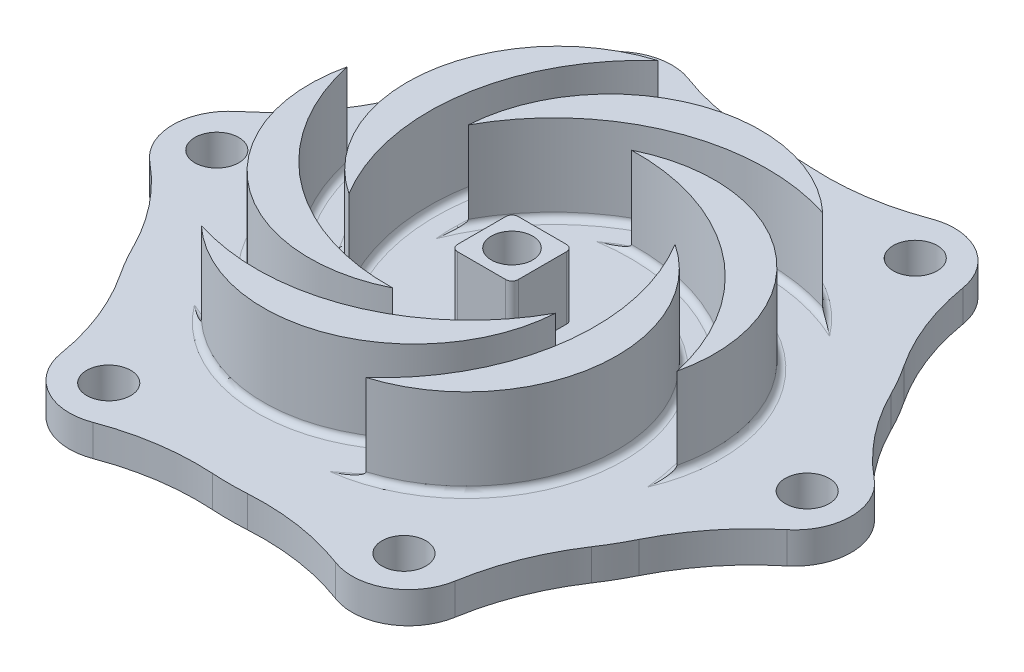
SolidWorks part; units mm, degrees
ref_plane "Front Plane" through (0, 0, 0) normal (0, 0, 1) x (1, 0, 0)
ref_plane "Top Plane" through (0, 0, 0) normal (0, 1, 0) x (1, 0, 0)
ref_plane "Right Plane" through (0, 0, 0) normal (1, 0, 0) x (0, 0, -1)
sketch "Sketch1" plane through (0, 0, 0) normal (0, 1, 0) x (1, 0, 0)
  circle A0 centre (0, 0) radius 25.4
  dimension "D1" = 50.8
extrude "Boss-Extrude1" add sketch "Sketch1" along normal blind 3.175
sketch "Sketch2" plane through (0, 0, 0) normal (0, -1, 0) x (-1, 0, 0)
  circle A0 centre (0, 0) radius 25.4
  circle A1 centre (0, 0) radius 28.575
  circle A2 centre (0, 0) radius 25.4 construction
  dimension "D1" = 3.175
extrude "Boss-Extrude2" add sketch "Sketch2" against normal up to surface (3.175 mm away) up to face at (0, 3.175, 25.4)
sketch "Sketch4" plane through (0, 3.175, 0) normal (0, 1, 0) x (1, 0, 0)
  line L1 (-2.4384, 3.0734) -> (2.4384, 3.0734)
  line L2 (-3.0734, 2.4384) -> (-3.0734, -2.4384)
  line L3 (-2.4384, -3.0734) -> (2.4384, -3.0734)
  line L4 (3.0734, 2.4384) -> (3.0734, -2.4384)
  line L5 (-3.0734, 3.0734) -> (3.0734, -3.0734) construction
  line L6 (-3.0734, -3.0734) -> (3.0734, 3.0734) construction
  line L7 (3.2004, -2.5654) -> (3.2004, 2.5654) construction
  arc A0 (-3.0734, -2.4384) -> (-2.4384, -3.0734) centre (-2.4384, -2.4384) ccw
  arc A1 (2.4384, -3.0734) -> (3.0734, -2.4384) centre (2.4384, -2.4384) ccw
  arc A2 (2.4384, 3.0734) -> (3.0734, 2.4384) centre (2.4384, 2.4384) cw
  arc A3 (-2.4384, 3.0734) -> (-3.0734, 2.4384) centre (-2.4384, 2.4384) ccw
  circle A4 centre (0, 0) radius 2.0955
  point P0 (0, 0)
  dimension "D1" = 0.635
  dimension "D3" = 4.191
  dimension "D2" = 0.127
extrude "Boss-Extrude3" add sketch "Sketch4" along normal blind 6.35
sketch "Sketch5" plane through (0, 3.175, 0) normal (0, 1, 0) x (1, 0, 0)
  circle A0 centre (0, 0) radius 2.0955
  circle A2 centre (0, 0) radius 2.0955 construction
extrude "Cut-Extrude1" cut sketch "Sketch5" against normal through all both and the other way through all
sketch "Sketch6" plane through (0, 3.175, 0) normal (0, 1, 0) x (1, 0, 0)
  arc A5 (-10.4486, 6.0325) -> (15.1562, 16.2554) centre (4.7634, 5.1089) cw
  arc A6 (-10.4486, 6.0325) -> (15.1562, 16.2554) centre (8.5151, -4.2878) cw
  arc A7 (15.1562, 16.2554) -> (-10.4486, 6.0325) centre (4.7634, 5.1089) ccw construction
  arc A8 (15.1562, 16.2554) -> (-10.4486, 6.0325) centre (8.5151, -4.2878) ccw construction
extrude "Boss-Extrude4" add sketch "Sketch6" along normal up to surface (8.89 mm away)
fillet "Fillet1" radius 0.635 2 edges at (0.5096, 3.175, -15.7632) (-0.8876, 3.175, -19.2625)
pattern_circular "CirPattern1" count 6 over 360 about axis through (0, 0, 0) along (0, 1, 0) of "Fillet1", "Boss-Extrude4"
sketch "Sketch7" [suppressed] plane through (0, 3.175, 0) normal (0, 1, 0) x (1, 0, 0)
  arc A0 (-1.546, 12.4834) -> (4.71, 11.9847) centre (0.4656, -1.7703) cw
  arc A1 (4.71, 11.9847) -> (5.6828, 12.0141) centre (5.1535, 13.4219) ccw
  arc A2 (5.6828, 12.0141) -> (12.8507, 12.8218) centre (10.8656, -1.7703) cw
  arc A3 (12.8507, 12.8218) -> (13.9805, 15.4964) centre (13.0535, 14.3121) ccw
  arc A4 (13.9805, 15.4964) -> (-2.8275, 15.0284) centre (5.8118, 6.8148) ccw
  arc A5 (-2.8275, 15.0284) -> (-1.546, 12.4834) centre (-1.7562, 13.9727) ccw
  arc A6 (13.9805, 15.4964) -> (-2.8699, 14.9835) centre (5.8118, 6.8148) ccw construction
  arc A7 (12.8507, 12.8218) -> (13.9805, 15.4964) centre (13.0535, 14.3121) ccw construction
  arc A8 (12.8507, 12.8218) -> (5.6828, 12.0141) centre (10.8656, -1.7703) ccw construction
  arc A15 (4.71, 11.9847) -> (5.6828, 12.0141) centre (5.1535, 13.4219) ccw construction
  arc A16 (4.71, 11.9847) -> (-1.546, 12.4834) centre (0.4656, -1.7703) ccw construction
  arc A17 (-2.8699, 14.9835) -> (-1.546, 12.4834) centre (-1.7562, 13.9727) ccw construction
extrude "Boss-Extrude5" [suppressed] add sketch "Sketch7" along normal up to surface (8.89 mm away)
fillet "Fillet3" [suppressed] radius 0.635
pattern_circular "CirPattern2" [suppressed] count 6 over 360
sketch "Sketch8" plane through (0, 3.175, 0) normal (0, 1, 0) x (1, 0, 0)
  line L0 (-28.575, 0) -> (0, 0) construction
  arc A0 (-28.0035, 5.6864) -> (-28.0035, -5.6864) centre (-28.575, 0) ccw
  circle A1 centre (0, 0) radius 28.575 construction
  arc A2 (-28.0035, -5.6864) -> (-28.0035, 5.6864) centre (0, 0) cw
  dimension "D1" = 11.43
extrude "Boss-Extrude6" add sketch "Sketch8" against normal up to surface (3.175 mm away) up to face at (0, 0, 2.0955)
fillet "Fillet4" radius 25.4 2 edges at (-28.0035, 1.5875, 5.6864) (-28.0035, 1.5875, -5.6864)
sketch "Sketch9" plane through (0, 3.175, 0) normal (0, 1, 0) x (1, 0, 0)
  line L0 (-34.29, 0) -> (-25.4, 0) construction
  circle A0 centre (-29.845, 0) radius 2.2225
  arc A1 (-32.2023, 4.4163) -> (-32.2023, -4.4163) centre (-28.575, 0) ccw construction
  circle A2 centre (0, 0) radius 25.4 construction
  dimension "D1" = 4.445
extrude "Cut-Extrude2" cut sketch "Sketch9" against normal through all both and the other way through all
pattern_circular "CirPattern3" count 6 over 360 about axis through (0, 0, 0) along (0, 1, 0) of "Boss-Extrude6", "Fillet4", "Cut-Extrude2"
